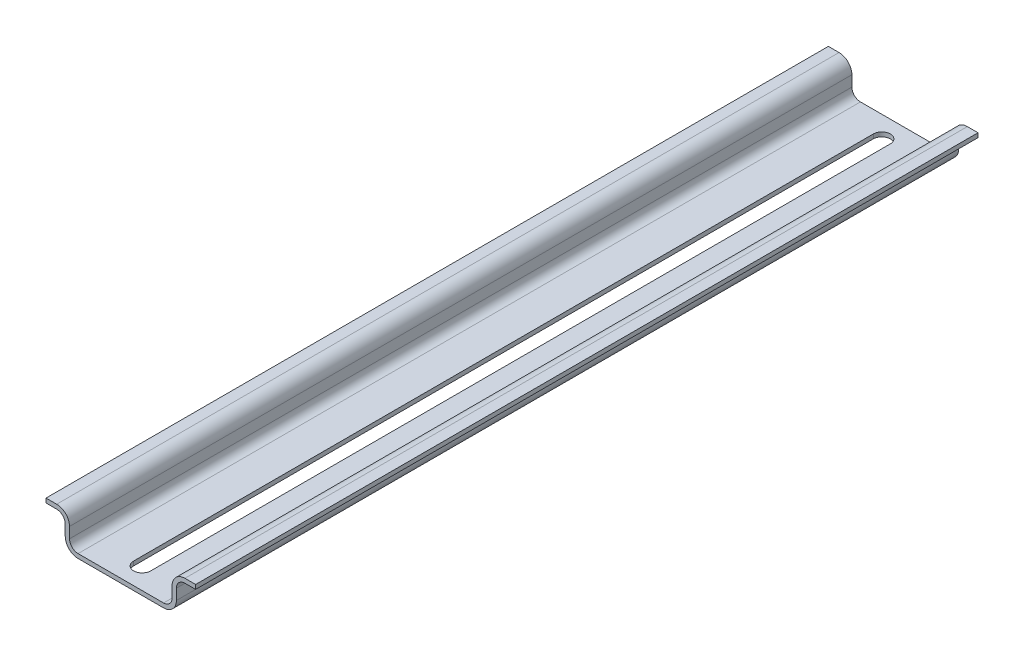
SolidWorks part; units mm, degrees
ref_plane "Front Plane" through (0, 0, 0) normal (0, 0, 1) x (1, 0, 0)
ref_plane "Top Plane" through (0, 0, 0) normal (0, 1, 0) x (1, 0, 0)
ref_plane "Right Plane" through (0, 0, 0) normal (1, 0, 0) x (0, 0, -1)
sketch "Sketch1" plane through (0, 0, 0) normal (0, 0, 1) x (1, 0, 0)
  line L0 (0, -2.7229) -> (2.5, -2.7229)
  line L1 (0, -2.2229) -> (2.5, -2.2229) construction
  line L2 (5, -4.7229) -> (5, -7.2229) construction
  line L3 (7.5, -9.7229) -> (17.5, -9.7229) construction
  line L4 (4.5, -4.7229) -> (4.5, -7.2229)
  line L5 (7.5, -10.2229) -> (17.5, -10.2229)
  line L6 (0, -1.7229) -> (2.5, -1.7229)
  line L7 (5.5, -4.7229) -> (5.5, -7.2229)
  line L8 (7.5, -9.2229) -> (17.5, -9.2229)
  line L9 (0, -1.7229) -> (0, -2.7229)
  line L10 (17.5, -9.2229) -> (17.5, -10.2229) construction
  line L11 (27.5, -9.7229) -> (17.5, -9.7229) construction
  line L12 (30, -4.7229) -> (30, -7.2229) construction
  line L13 (35, -2.2229) -> (32.5, -2.2229) construction
  line L14 (35, -1.7229) -> (35, -2.7229)
  line L15 (27.5, -9.2229) -> (17.5, -9.2229)
  line L16 (29.5, -4.7229) -> (29.5, -7.2229)
  line L17 (35, -1.7229) -> (32.5, -1.7229)
  line L18 (27.5, -10.2229) -> (17.5, -10.2229)
  line L19 (30.5, -4.7229) -> (30.5, -7.2229)
  line L20 (35, -2.7229) -> (32.5, -2.7229)
  arc A0 (7.5, -9.7229) -> (5, -7.2229) centre (7.5, -7.2229) cw construction
  arc A1 (5, -4.7229) -> (2.5, -2.2229) centre (2.5, -4.7229) ccw construction
  arc A2 (4.5, -4.7229) -> (2.5, -2.7229) centre (2.5, -4.7229) ccw
  arc A3 (7.5, -10.2229) -> (4.5, -7.2229) centre (7.5, -7.2229) cw
  arc A4 (5.5, -4.7229) -> (2.5, -1.7229) centre (2.5, -4.7229) ccw
  arc A5 (7.5, -9.2229) -> (5.5, -7.2229) centre (7.5, -7.2229) cw
  arc A6 (30, -4.7229) -> (32.5, -2.2229) centre (32.5, -4.7229) cw construction
  arc A7 (27.5, -9.7229) -> (30, -7.2229) centre (27.5, -7.2229) ccw construction
  arc A8 (27.5, -9.2229) -> (29.5, -7.2229) centre (27.5, -7.2229) ccw
  arc A9 (29.5, -4.7229) -> (32.5, -1.7229) centre (32.5, -4.7229) cw
  arc A10 (27.5, -10.2229) -> (30.5, -7.2229) centre (27.5, -7.2229) ccw
  arc A11 (30.5, -4.7229) -> (32.5, -2.7229) centre (32.5, -4.7229) cw
  dimension "D1" = 2.5
  dimension "D2" = 17.5
  dimension "D3" = 5
  dimension "D4" = 7.5
  dimension "D5" = 0.5
  dimension "D6" = 0.5
extrude "Boss-Extrude1" add sketch "Sketch1" along normal blind 183
sketch "Sketch2" plane through (0, -9.2229, 0) normal (0, 1, 0) x (1, 0, 0)
  line L0 (17.5, -183) -> (17.5, 0) construction
  line L1 (27.5, -183) -> (7.5, -183) construction
  line L2 (27.5, 0) -> (7.5, 0) construction
  line L3 (17.5, -178) -> (17.5, -5) construction
  line L4 (15.5, -178) -> (15.5, -5)
  line L5 (19.5, -178) -> (19.5, -5)
  arc A0 (15.5, -178) -> (19.5, -178) centre (17.5, -178) ccw
  arc A1 (19.5, -5) -> (15.5, -5) centre (17.5, -5) ccw
  point P8 (17.5, -91.5)
  dimension "D1" = 5
  dimension "D2" = 5
  dimension "D3" = 4
extrude "Cut-Extrude1" cut sketch "Sketch2" against normal up to next
